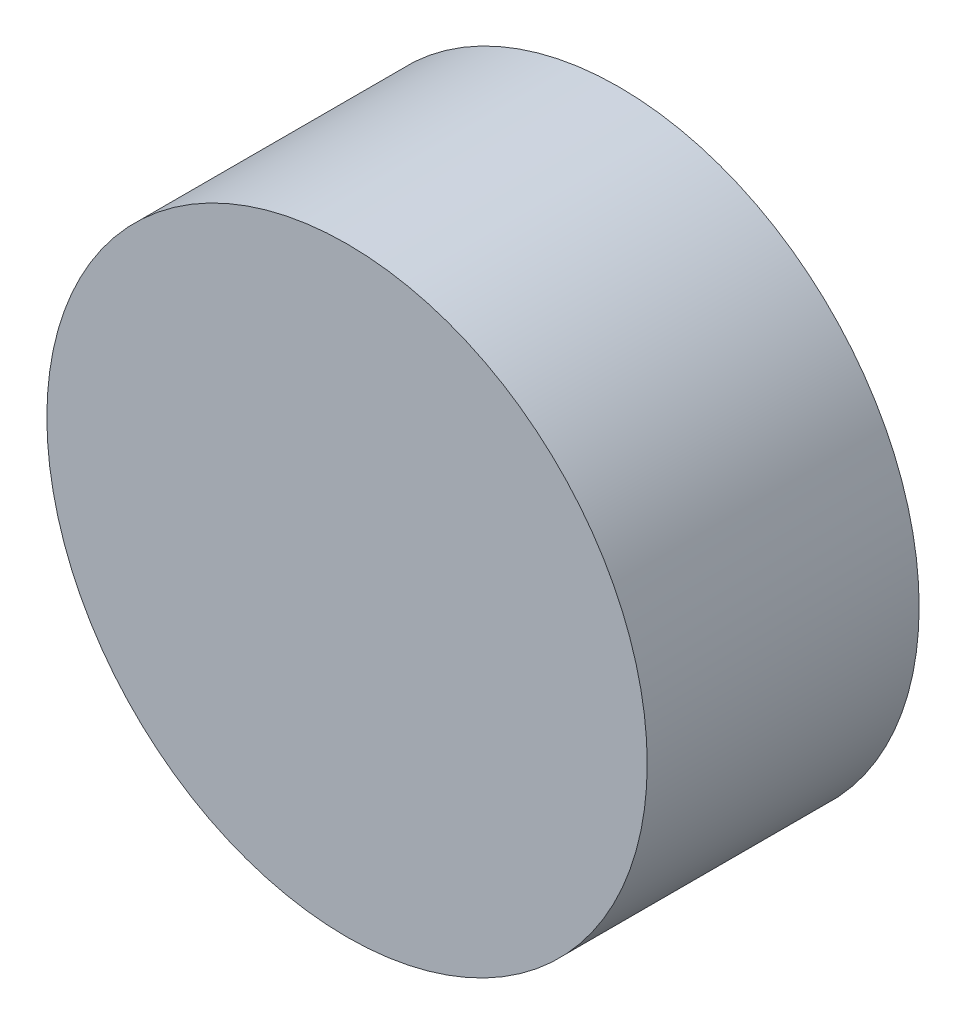
SolidWorks part; units mm, degrees
material "0.6025 (EN-GJL-250)"
ref_plane "Alzado" through (0, 0, 0) normal (0, 0, 1) x (1, 0, 0)
ref_plane "Planta" through (0, 0, 0) normal (0, 1, 0) x (1, 0, 0)
ref_plane "Vista lateral" through (0, 0, 0) normal (1, 0, 0) x (0, 0, -1)
sketch "Croquis1" plane through (0, 0, 0) normal (0, 0, 1) x (1, 0, 0)
  circle A0 centre (0, 0) radius 17
  dimension "D1" = 34
extrude "Saliente-Extruir1" add sketch "Croquis1" along normal blind 15.4
